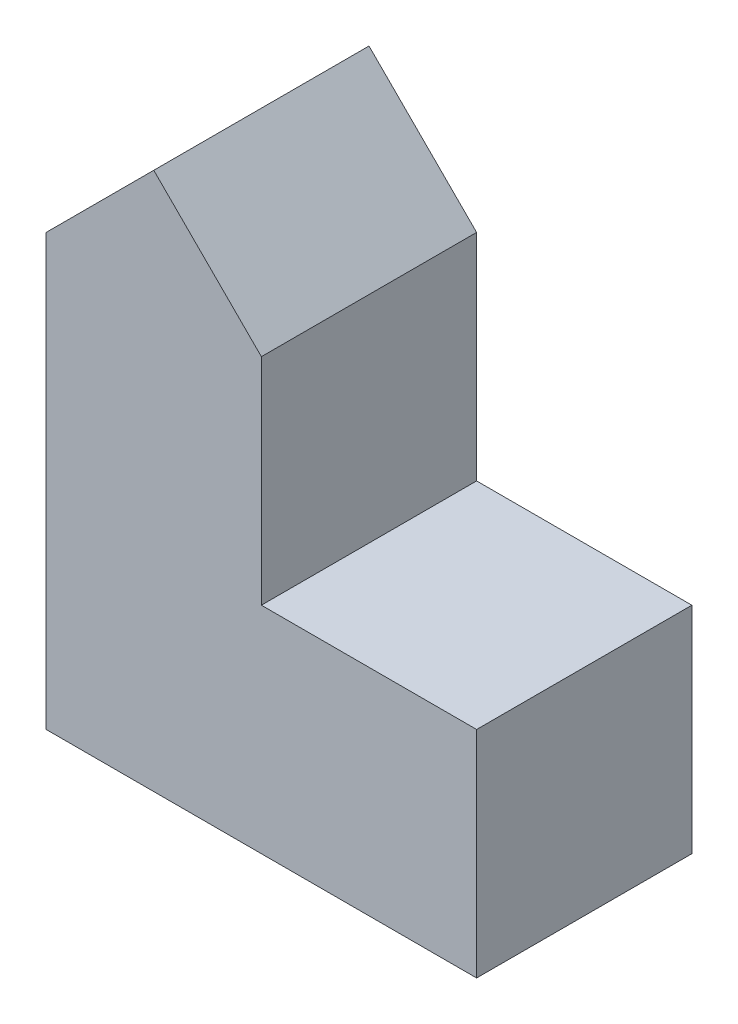
SolidWorks part; units mm, degrees
ref_plane "Front Plane" through (0, 0, 0) normal (0, 0, 1) x (1, 0, 0)
ref_plane "Top Plane" through (0, 0, 0) normal (0, 1, 0) x (1, 0, 0)
ref_plane "Right Plane" through (0, 0, 0) normal (1, 0, 0) x (0, 0, -1)
sketch "Sketch1" plane through (0, 0, 0) normal (0, 0, 1) x (1, 0, 0)
  line L0 (0, 0) -> (20, 0)
  line L1 (20, 0) -> (20, 10)
  line L2 (20, 10) -> (10, 10)
  line L3 (10, 10) -> (10, 20)
  line L4 (10, 20) -> (5, 25)
  line L5 (5, 25) -> (0, 20)
  line L6 (0, 20) -> (0, 0)
  dimension "D1" = 20
  dimension "D2" = 10
  dimension "D3" = 10
  dimension "D4" = 20
  dimension "D5" = 90
  dimension "D6" = 10
  dimension "D7" = 5
extrude "Boss-Extrude1" add sketch "Sketch1" along normal blind 10
